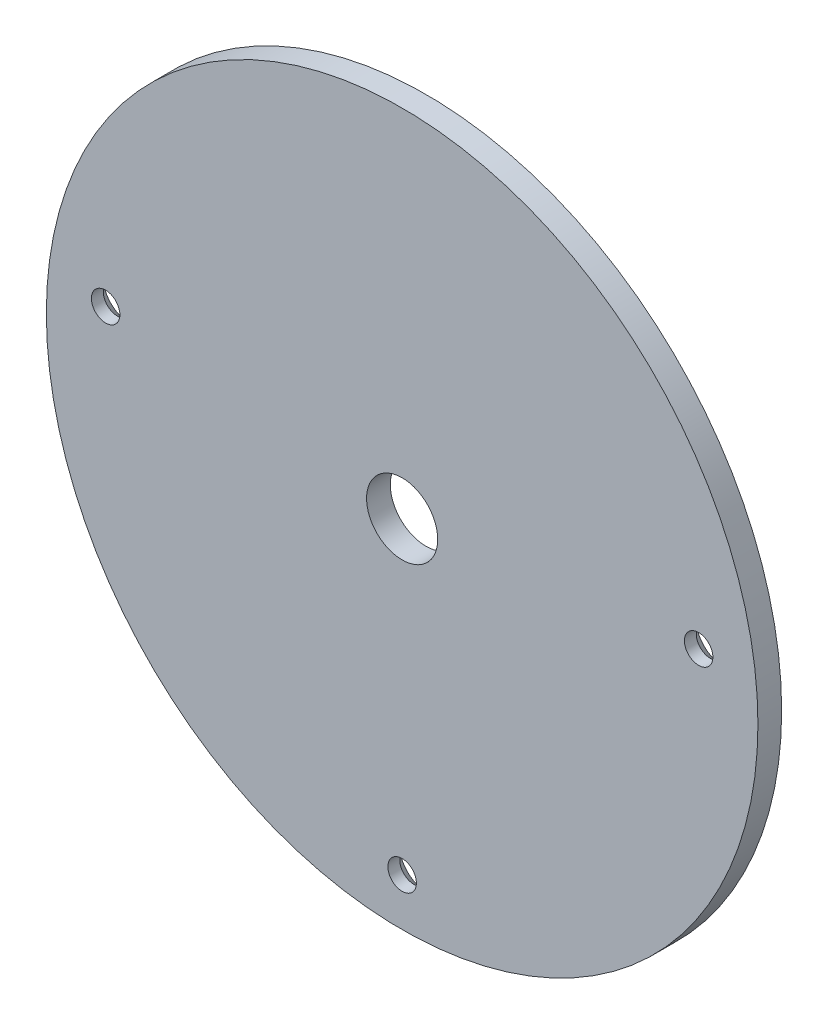
SolidWorks part; units mm, degrees
ref_plane "Piano frontale" through (0, 0, 0) normal (0, 0, 1) x (1, 0, 0)
ref_plane "Piano superiore" through (0, 0, 0) normal (0, 1, 0) x (1, 0, 0)
ref_plane "Piano destro" through (0, 0, 0) normal (1, 0, 0) x (0, 0, -1)
sketch "Schizzo1" plane through (0, 0, 0) normal (0, 0, 1) x (1, 0, 0)
  circle A0 centre (0, 0) radius 30
  circle A1 centre (0, 0) radius 3
  dimension "D1" = 60
  dimension "D2" = 6
extrude "Estrusione-Estrusione1" add sketch "Schizzo1" along normal blind 2
hole_wizard "Foro svasato per Vite M2-1" positions "Schizzo3" profile "Schizzo4" countersink size "M2" standard "ISO"
sketch "Schizzo3" plane through (0, 0, 0) normal (0, 0, -1) x (-1, 0, 0)
  line L0 (0, 30) -> (0, -30) construction
  circle A0 centre (0, 0) radius 30 construction
  point P0 (0, -26)
  point P2 (-25, 3)
  point P4 (25, 3)
  dimension "D1" = 50
  dimension "D2" = 3
  dimension "D3" = 26
sketch "Schizzo4" plane through (0, -26, 0) normal (1, 0, 0) x (0, 1, 0)
  line L0 (0, 0) -> (0, 6.721)
  line L1 (0, 6.721) -> (1.2, 6)
  line L2 (1.2, 6) -> (1.2, 1)
  line L3 (1.2, 1) -> (2.2, 0)
  line L5 (2.2, 0) -> (0, 0)
  line L6 (-1.2, 1) -> (-2.2, 0) construction
  line L10 (0, 6.721) -> (-1.2, 6) construction
  line L11 (0, -6.35) -> (0, 107.95) construction
  dimension "Hole Dia." = 2.4
  dimension "Hole Depth" = 6
  dimension "Near C'Sink Dia." = 4.4
  dimension "Near C'Sink Angle" = 90
  dimension "Drill Angle" = 118
